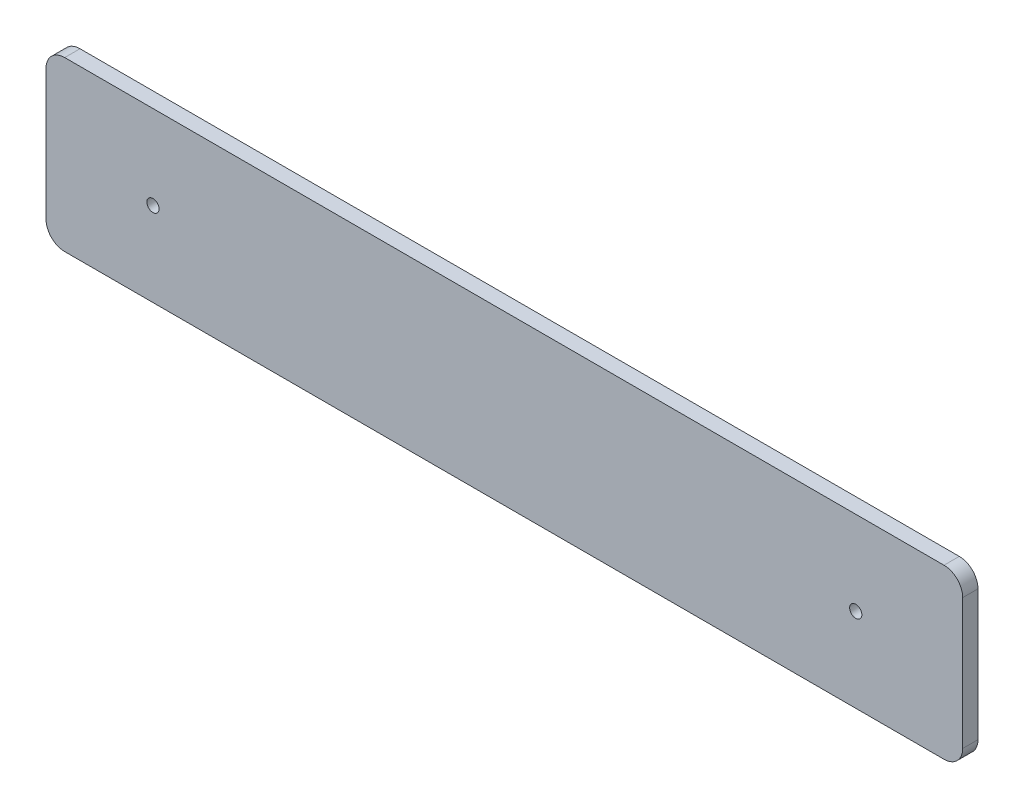
SolidWorks part; units mm, degrees
ref_plane "Front Plane" through (0, 0, 0) normal (0, 0, 1) x (1, 0, 0)
ref_plane "Top Plane" through (0, 0, 0) normal (0, 1, 0) x (1, 0, 0)
ref_plane "Right Plane" through (0, 0, 0) normal (1, 0, 0) x (0, 0, -1)
sketch "Sketch2" plane through (0, 0, 0) normal (0, 0, 1) x (1, 0, 0)
  line L0 (1.2247, 0) -> (58.7753, 0)
  line L1 (0, -1.2247) -> (0, -9.7753)
  line L2 (1.2247, -11) -> (58.7753, -11)
  line L3 (60, -9.7753) -> (60, -1.2247)
  line L4 (0, -5.5) -> (7, -5.5) construction
  line L5 (60, -5.5) -> (53, -5.5) construction
  line L6 (7, -5.5) -> (7.4, -5.5) construction
  line L7 (0, -5.5) -> (60, -5.5) construction
  line L8 (30, 0) -> (30, -11) construction
  circle A0 centre (7, -5.5) radius 0.4
  arc A1 (1.2247, 0) -> (0, -1.2247) centre (1.2247, -1.2247) ccw
  arc A2 (58.7753, 0) -> (60, -1.2247) centre (58.7753, -1.2247) cw
  circle A3 centre (53, -5.5) radius 0.4
  arc A4 (58.7753, -11) -> (60, -9.7753) centre (58.7753, -9.7753) ccw
  arc A5 (1.2247, -11) -> (0, -9.7753) centre (1.2247, -9.7753) cw
  dimension "D5" = 0.4
  dimension "D3" = 7
  dimension "D4" = 7
extrude "Boss-Extrude1" add sketch "Sketch2" along normal blind 1
